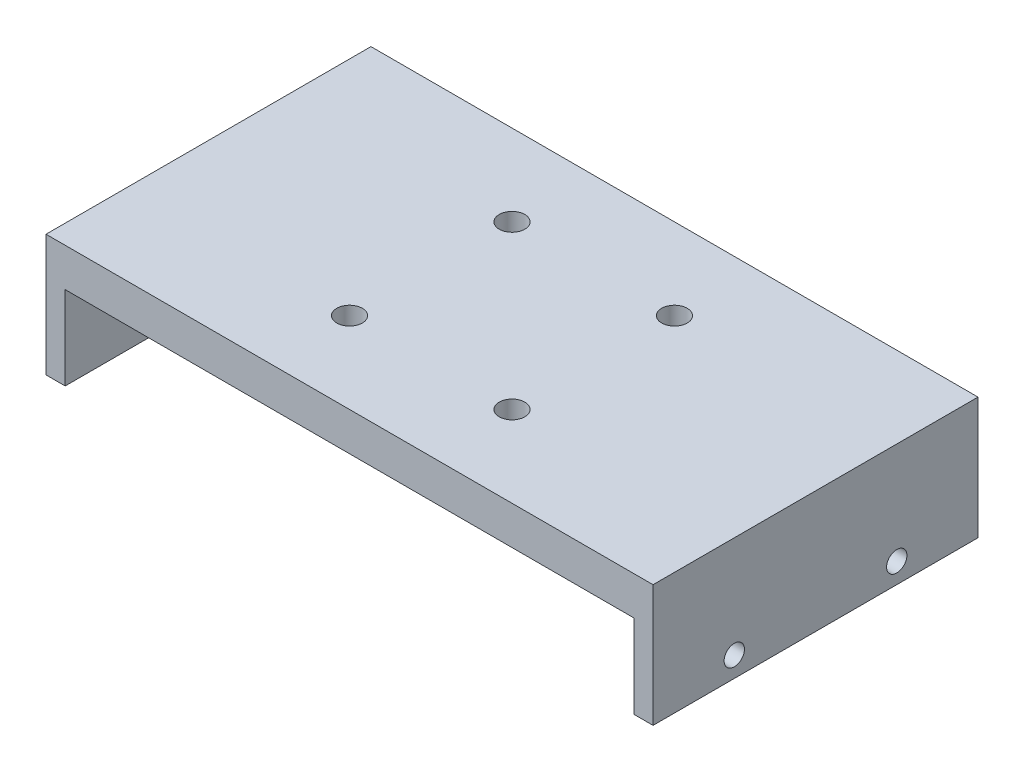
SolidWorks part; units mm, degrees
ref_plane "Front Plane" through (0, 0, 0) normal (0, 0, 1) x (1, 0, 0)
ref_plane "Top Plane" through (0, 0, 0) normal (0, 1, 0) x (1, 0, 0)
ref_plane "Right Plane" through (0, 0, 0) normal (1, 0, 0) x (0, 0, -1)
sketch "Sketch1" plane through (0, 0, 0) normal (0, 1, 0) x (1, 0, 0)
  line L1 (-44.45, -25.4) -> (44.45, -25.4)
  line L2 (-44.45, -25.4) -> (-44.45, 25.4)
  line L3 (-44.45, 25.4) -> (44.45, 25.4)
  line L4 (44.45, -25.4) -> (44.45, 25.4)
  line L5 (-44.45, -25.4) -> (44.45, 25.4) construction
  line L6 (-44.45, 25.4) -> (44.45, -25.4) construction
  point P0 (0, 0)
  dimension "D1" = 50.8
  dimension "D2" = 88.9
extrude "Boss-Extrude1" add sketch "Sketch1" along normal blind 6
sketch "Sketch2" plane through (-44.45, 0, 0) normal (-1, 0, 0) x (0, 0, 1)
  line L1 (-25.4, 6) -> (25.4, 6)
  line L2 (-25.4, 6) -> (-25.4, -13.05)
  line L3 (-25.4, -13.05) -> (25.4, -13.05)
  line L4 (25.4, 6) -> (25.4, -13.05)
  dimension "D1" = 19.05
extrude "Boss-Extrude2" add sketch "Sketch2" along normal blind 3
sketch "Sketch3" plane through (-47.45, 0, 0) normal (-1, 0, 0) x (0, 0, 1)
  line L0 (-25.4, -13.05) -> (25.4, -13.05) construction
  circle A4 centre (-12.7, -9.875) radius 1.5875
  circle A5 centre (12.7, -9.875) radius 1.5875
  dimension "D2" = 3.175
  dimension "D3" = 3.175
  dimension "D1" = 3.175
  dimension "D4" = 12.7
  dimension "D5" = 12.7
extrude "Cut-Extrude1" cut sketch "Sketch3" against normal through all
mirror "Mirror1" about plane through (0, 0, 0) normal (1, 0, 0) of "Cut-Extrude1", "Boss-Extrude2"
sketch "Sketch4" plane through (0, 6, 0) normal (0, 1, 0) x (1, 0, 0)
  line L1 (-12.7, -12.7) -> (12.7, -12.7) construction
  line L2 (-12.7, -12.7) -> (-12.7, 12.7) construction
  line L3 (-12.7, 12.7) -> (12.7, 12.7) construction
  line L4 (12.7, -12.7) -> (12.7, 12.7) construction
  line L5 (-12.7, -12.7) -> (12.7, 12.7) construction
  line L6 (-12.7, 12.7) -> (12.7, -12.7) construction
  circle A0 centre (-12.7, 12.7) radius 2
  circle A1 centre (12.7, 12.7) radius 2
  circle A2 centre (-12.7, -12.7) radius 2
  circle A3 centre (12.7, -12.7) radius 2
  point P0 (0, 0)
  dimension "D3" = 4
  dimension "D4" = 4
  dimension "D5" = 4
  dimension "D6" = 4
  dimension "D1" = 25.4
  dimension "D2" = 25.4
extrude "Cut-Extrude2" cut sketch "Sketch4" against normal through all
